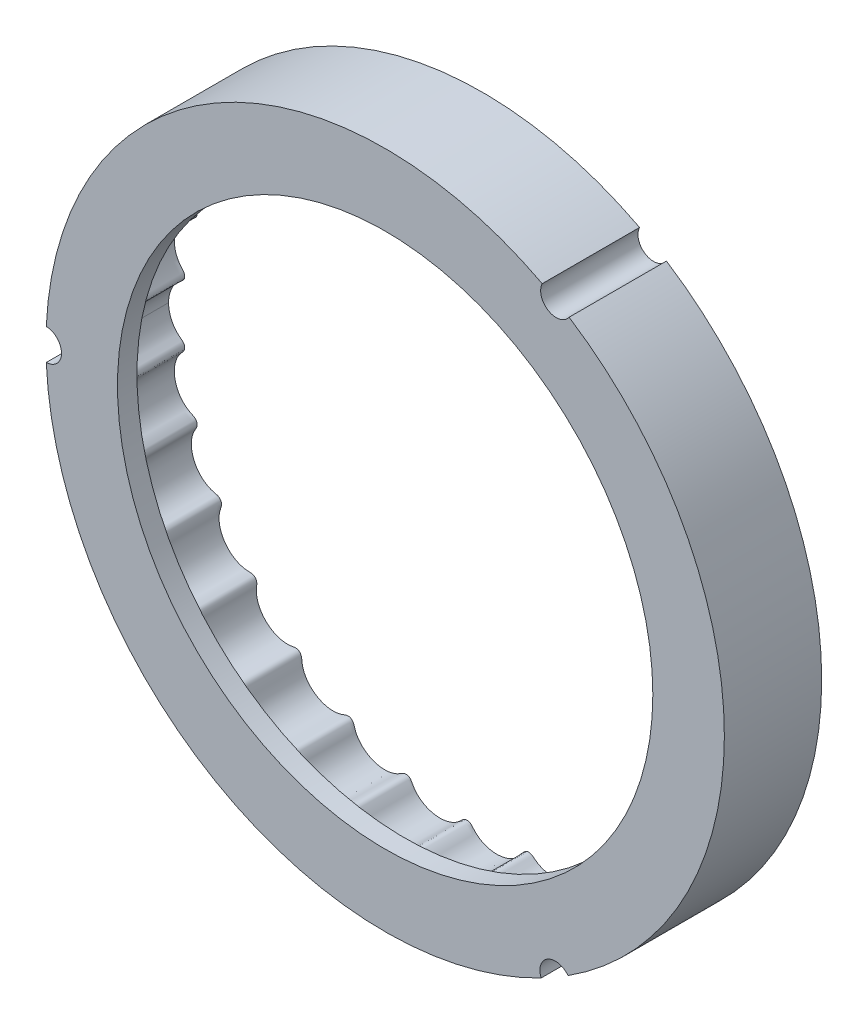
SolidWorks part; units mm, degrees
ref_plane "Plan de face" through (0, 0, 0) normal (0, 0, 1) x (1, 0, 0)
ref_plane "Plan de dessus" through (0, 0, 0) normal (0, 1, 0) x (1, 0, 0)
ref_plane "Plan de droite" through (0, 0, 0) normal (1, 0, 0) x (0, 0, -1)
sketch "Esquisse1" plane through (0, 0, 0) normal (0, 0, 1) x (1, 0, 0)
  line L0 (-1000, 0) -> (49000, 0) construction
  circle A1 centre (0, 0) radius 34.85
  spline S0 degree 4 poles (30.9263, 8.5917) (30.9244, 8.4726) (30.9128, 8.294) (30.8795, 8.0576) (30.8075, 7.7682) (30.7313, 7.5422) (30.6363, 7.3233) (30.5223, 7.1138) (30.4005, 6.9287) (30.2778, 6.7655) (30.1754, 6.608) (30.1146, 6.4469) (30.0971, 6.2542) (30.1421, 6.0755) (30.2337, 5.9301) (30.3636, 5.8076) (30.4814, 5.7308) (30.5967, 5.6632) (30.7272, 5.5824) (30.8546, 5.4968) (31.0375, 5.3568) (31.2617, 5.1464) (31.5493, 4.8022) (31.8437, 4.2901) (32.0606, 3.6436) (32.1377, 2.876) (32.0537, 2.1997) (31.8673, 1.6401) (31.6545, 1.2467) (31.4775, 0.9968) (31.3101, 0.8048) (31.1655, 0.661) (31.0397, 0.5491) (30.944, 0.4561) (30.882, 0.3799) (30.8461, 0.3281) (30.8149, 0.2732) (30.7893, 0.2154) (30.772, 0.1642) (30.7612, 0.1176) (30.7537, 0.0676) (30.7495, 0.0174) (30.7494, -0.0196) (30.7554, -0.0873) (30.767, -0.1466) (30.7842, -0.2016) (30.8067, -0.2559) (30.8409, -0.3211) (30.8874, -0.3891) (30.9471, -0.4581) (31.0185, -0.528) (31.0876, -0.5916) (31.174, -0.6713) (31.275, -0.7696) (31.4187, -0.925) (31.5905, -1.1493) (31.7652, -1.4406) (31.9227, -1.8045) (32.035, -2.1949) (32.0985, -2.6058) (32.1109, -3.0185) (32.074, -3.4266) (31.9897, -3.8245) (31.8596, -4.2068) (31.6858, -4.5663) (31.471, -4.8977) (31.2491, -5.1584) (31.0376, -5.3559) (30.847, -5.5028) (30.6865, -5.6097) (30.5113, -5.713) (30.3279, -5.8265) (30.1731, -5.9986) (30.0932, -6.2291) (30.1102, -6.46) (30.2005, -6.6565) (30.3192, -6.8188) (30.4296, -6.9724) (30.5569, -7.1717) (30.687, -7.4243) (30.8105, -7.7521) (30.9023, -8.158) (30.9393, -8.591) (30.9154, -9.0432) (30.8331, -9.4792) (30.6986, -9.8922) (30.5175, -10.2769) (30.2954, -10.6287) (30.0366, -10.942) (29.747, -11.2129) (29.4704, -11.4101) (29.2233, -11.5472) (29.008, -11.6414) (28.8315, -11.7068) (28.6421, -11.7692) (28.45, -11.8631) (28.2883, -12.027) (28.2103, -12.2249) (28.2035, -12.4054) (28.2368, -12.5701) (28.2938, -12.7158) (28.368, -12.8732) (28.4417, -13.0514) (28.5193, -13.2794) (28.5859, -13.5612) (28.6259, -13.9014) (28.6202, -14.2968) (28.5642, -14.6927) (28.4589, -15.0831) (28.3079, -15.4581) (28.1138, -15.8126) (27.8795, -16.1417) (27.6077, -16.4405) (27.3049, -16.7011) (26.9756, -16.9193) (26.6681, -17.0697) (26.3953, -17.1663) (26.1618, -17.2248) (25.972, -17.2589) (25.7701, -17.2839) (25.5569, -17.3186) (25.349, -17.4213) (25.1897, -17.6061) (25.1202, -17.827) (25.1307, -18.0426) (25.1768, -18.2381) (25.2169, -18.423) (25.254, -18.6564) (25.2723, -18.9399) (25.2546, -19.2896) (25.1768, -19.6983) (25.0382, -20.11) (24.8361, -20.5151) (24.5838, -20.8868) (24.2876, -21.2199) (23.9535, -21.5097) (23.5874, -21.7517) (23.2101, -21.9337) (22.8739, -22.0436) (22.5914, -22.1021) (22.3252, -22.1336) (22.1016, -22.1407) (21.8785, -22.1275) (21.6437, -22.1096) (21.4389, -22.1288) (21.235, -22.2214) (21.0721, -22.3967) (20.993, -22.6129) (20.9856, -22.8294) (20.9927, -23.0328) (20.9891, -23.2256) (20.9691, -23.4656) (20.9175, -23.7504) (20.8184, -24.0782) (20.6555, -24.4384) (20.4463, -24.779) (20.1313, -25.174) (19.6816, -25.5833) (19.1591, -25.8987) (18.5904, -26.1016) (18.1017, -26.1879) (17.7596, -26.203) (17.4709, -26.1826) (17.2335, -26.1428) (17.0458, -26.0984) (16.8505, -26.0411) (16.6399, -25.9918) (16.4106, -26.0101) (16.1979, -26.12) (16.0541, -26.2917) (15.9812, -26.4843) (15.9468, -26.6722) (15.9136, -26.8477) (15.8717, -27.0214) (15.8184, -27.1921) (15.7382, -27.4006) (15.5637, -27.7585) (15.2945, -28.1386) (14.9171, -28.5115) (14.4633, -28.8259) (14.0673, -29.0303) (13.6447, -29.1826) (13.2023, -29.278) (12.7692, -29.3104) (12.354, -29.2847) (12.0109, -29.2154) (11.7407, -29.1278) (11.5237, -29.0341) (11.3545, -28.9495) (11.1772, -28.8554) (10.9723, -28.7881) (10.7409, -28.7959) (10.5202, -28.8997) (10.3654, -29.0728) (10.2765, -29.2698) (10.2021, -29.4592) (10.1221, -29.6346) (10.0078, -29.8465) (9.8467, -30.087) (9.625, -30.3479) (9.2571, -30.6809) (8.748, -31.0055) (8.1785, -31.2248) (7.5795, -31.329) (7.0742, -31.3356) (6.6768, -31.2918) (6.2924, -31.1996) (5.9727, -31.0767) (5.7161, -30.9427) (5.5144, -30.8112) (5.3599, -30.6957) (5.2035, -30.5655) (5.0269, -30.4397) (4.8069, -30.3718) (4.5688, -30.3956) (4.3717, -30.5019) (4.2324, -30.653) (4.1276, -30.8125) (4.0272, -30.9603) (3.9195, -31.1029) (3.8025, -31.238) (3.6457, -31.3971) (3.3428, -31.6554) (2.8502, -31.9535) (2.2369, -32.1596) (1.5733, -32.2322) (1.0155, -32.1965) (0.5716, -32.1077) (0.1613, -31.9647) (-0.2092, -31.7754) (-0.4962, -31.5747) (-0.7089, -31.3863) (-0.8705, -31.2138) (-0.9919, -31.0688) (-1.1186, -30.9128) (-1.2838, -30.7736) (-1.5018, -30.6954) (-1.7453, -30.7105) (-1.9528, -30.8138) (-2.1099, -30.9617) (-2.2535, -31.1059) (-2.3968, -31.2349) (-2.5863, -31.3834) (-2.8299, -31.5395) (-3.1373, -31.6901) (-3.5116, -31.8163) (-3.9031, -31.8956) (-4.3058, -31.9269) (-4.7094, -31.9102) (-5.1084, -31.8461) (-5.4973, -31.7354) (-5.8703, -31.5791) (-6.2174, -31.3804) (-6.5332, -31.1424) (-6.7773, -30.902) (-6.9589, -30.6765) (-7.0914, -30.4753) (-7.1869, -30.3078) (-7.2659, -30.1527) (-7.3469, -30.0188) (-7.4577, -29.8924) (-7.6055, -29.7886) (-7.8103, -29.7311) (-8.0386, -29.7607) (-8.2296, -29.8563) (-8.3948, -29.9679) (-8.5547, -30.0672) (-8.7612, -30.1794) (-9.0211, -30.2905) (-9.3464, -30.3878) (-9.7381, -30.4504) (-10.1442, -30.4625) (-10.5582, -30.4222) (-10.9731, -30.3294) (-11.3818, -30.1823) (-11.7767, -29.98) (-12.1486, -29.7215) (-12.4679, -29.4266) (-12.7322, -29.1051) (-12.9152, -28.8064) (-13.0349, -28.5486) (-13.1142, -28.3258) (-13.1678, -28.1444) (-13.224, -27.9513) (-13.3256, -27.7603) (-13.4992, -27.6071) (-13.731, -27.5313) (-13.9616, -27.5503) (-14.1632, -27.6266) (-14.3522, -27.7017) (-14.535, -27.7628) (-14.7681, -27.8232) (-15.0538, -27.869) (-15.3957, -27.8843) (-15.7892, -27.8507) (-16.2785, -27.7463) (-16.7528, -27.5609) (-17.1946, -27.3015) (-17.5907, -26.9743) (-17.8764, -26.672) (-18.1159, -26.3439) (-18.3067, -25.9962) (-18.4295, -25.6796) (-18.5013, -25.4063) (-18.5394, -25.1743) (-18.559, -24.9871) (-18.5718, -24.7882) (-18.6117, -24.5785) (-18.7262, -24.3789) (-18.8959, -24.2506) (-19.068, -24.1957) (-19.2358, -24.1842) (-19.3915, -24.2014) (-19.5625, -24.2339) (-19.7534, -24.2613) (-19.9935, -24.2801) (-20.283, -24.2751) (-20.6226, -24.2297) (-21.0043, -24.1264) (-21.3741, -23.9741) (-21.7265, -23.7753) (-22.0523, -23.536) (-22.3477, -23.2602) (-22.6084, -22.9516) (-22.8306, -22.6144) (-23.008, -22.2566) (-23.138, -21.8836) (-23.2077, -21.5484) (-23.2339, -21.2603) (-23.2329, -21.0195) (-23.2189, -20.8273) (-23.1931, -20.6255) (-23.1714, -20.4109) (-23.2147, -20.1833) (-23.35, -19.9802) (-23.5441, -19.854) (-23.755, -19.8069) (-23.956, -19.8018) (-24.145, -19.7948) (-24.3804, -19.7731) (-24.6597, -19.7208) (-25.1025, -19.5837) (-25.5719, -19.3339) (-26.0033, -18.993) (-26.3759, -18.5716) (-26.6251, -18.2022) (-26.8231, -17.8067) (-26.9668, -17.3922) (-27.0498, -16.9817) (-27.0732, -16.6288) (-27.06, -16.3406) (-27.0307, -16.1192) (-26.9958, -15.9439) (-26.9493, -15.7714) (-26.894, -15.6014) (-26.8318, -15.421) (-26.7962, -15.2188) (-26.8307, -14.9976) (-26.9558, -14.7937) (-27.1431, -14.6595) (-27.3504, -14.5957) (-27.5492, -14.5518) (-27.7351, -14.5006) (-27.9627, -14.422) (-28.2261, -14.3016) (-28.5192, -14.1246) (-28.8279, -13.8775) (-29.1063, -13.5905) (-29.4109, -13.1873) (-29.6486, -12.7398) (-29.8135, -12.2607) (-29.9002, -11.7631) (-29.9203, -11.3641) (-29.8906, -10.9701) (-29.8207, -10.6349) (-29.7296, -10.3602) (-29.6324, -10.14) (-29.543, -9.9692) (-29.4389, -9.7943) (-29.3367, -9.6039) (-29.2926, -9.3762) (-29.3434, -9.1376) (-29.4773, -8.9486) (-29.655, -8.8263) (-29.838, -8.7434) (-30.0085, -8.6617) (-30.2156, -8.5478) (-30.4507, -8.3882) (-30.716, -8.1598) (-30.9909, -7.8477) (-31.231, -7.4857) (-31.427, -7.0776) (-31.5659, -6.6505) (-31.6473, -6.2122) (-31.6713, -5.7706) (-31.638, -5.3329) (-31.5503, -4.9233) (-31.4308, -4.5902) (-31.3037, -4.3313) (-31.1883, -4.14) (-31.0862, -3.9932) (-30.9747, -3.8536) (-30.8564, -3.7197) (-30.7286, -3.5777) (-30.6197, -3.4032) (-30.57, -3.1848) (-30.6111, -2.949) (-30.7353, -2.7553) (-30.9027, -2.6179) (-31.0677, -2.4988) (-31.2178, -2.3777) (-31.395, -2.2147) (-31.5882, -1.9992) (-31.757, -1.7611) (-31.8999, -1.5043) (-32.0017, -1.2787) (-32.0729, -1.0898) (-32.1322, -0.8972) (-32.1797, -0.7008) (-32.2109, -0.5276) (-32.2302, -0.3771) (-32.2413, -0.2512) (-32.2473, -0.1576) (-32.2503, -0.0299) (-32.2502, 0.0388) (-32.2466, 0.1794) (-32.2393, 0.2769) (-32.2254, 0.4211) (-32.2015, 0.5861) (-32.1629, 0.7796) (-32.104, 0.996) (-32.0305, 1.2085) (-31.9423, 1.415) (-31.8234, 1.6465) (-31.6896, 1.8577) (-31.544, 2.0481) (-31.3892, 2.217) (-31.2566, 2.3437) (-31.1158, 2.461) (-30.9692, 2.571) (-30.8116, 2.6874) (-30.6684, 2.8431) (-30.5791, 3.0569) (-30.5824, 3.2743) (-30.648, 3.4491) (-30.7462, 3.5961) (-30.8554, 3.7195) (-30.9782, 3.8564) (-31.1043, 4.0167) (-31.2467, 4.228) (-31.3916, 4.4977) (-31.5524, 4.9075) (-31.6691, 5.4709) (-31.6776, 6.1306) (-31.5281, 6.8579) (-31.2314, 7.526) (-30.8027, 8.104) (-30.3929, 8.4476) (-30.0923, 8.62) (-29.937, 8.6951) knots 0 0 0 0 0 0.003562 0.005342 0.007123 0.008904 0.010685 0.012466 0.014247 0.015519 0.016792 0.018065 0.019337 0.021229 0.022175 0.02312 0.024649 0.025414 0.026178 0.027707 0.029236 0.032293 0.035351 0.04107 0.046788 0.052507 0.058226 0.06127 0.064314 0.065836 0.067358 0.06888 0.070402 0.070873 0.071343 0.071813 0.072284 0.072754 0.073224 0.073459 0.073695 0.074165 0.074604 0.075042 0.075481 0.07592 0.076358 0.076797 0.077674 0.078377 0.079079 0.079782 0.080484 0.081889 0.083294 0.086104 0.088914 0.092014 0.095114 0.098215 0.101315 0.104325 0.107336 0.110347 0.113357 0.116235 0.119112 0.12055 0.121989 0.123428 0.124866 0.12664 0.128414 0.130187 0.13196 0.133373 0.134786 0.1362 0.137613 0.140439 0.143265 0.146639 0.150014 0.153388 0.156763 0.159865 0.162966 0.166068 0.169169 0.171979 0.174789 0.176194 0.177599 0.179004 0.180409 0.182167 0.183924 0.185706 0.186596 0.187487 0.188927 0.190366 0.191805 0.193245 0.196124 0.199002 0.202017 0.205033 0.208048 0.211063 0.214074 0.217086 0.220098 0.22311 0.225987 0.228865 0.230303 0.231742 0.233181 0.234619 0.236396 0.238172 0.239944 0.241716 0.243129 0.244541 0.245954 0.247367 0.250192 0.253017 0.256391 0.259764 0.263137 0.266511 0.269782 0.273052 0.276323 0.279594 0.282264 0.283598 0.284933 0.287603 0.288938 0.290273 0.291978 0.293684 0.295463 0.297243 0.298682 0.300121 0.30156 0.302999 0.305877 0.308756 0.311769 0.314783 0.317797 0.323824 0.32985 0.332862 0.33574 0.338618 0.340058 0.341497 0.342936 0.344375 0.346152 0.34793 0.349637 0.351344 0.352679 0.354014 0.355349 0.356684 0.358019 0.359354 0.362024 0.368567 0.371839 0.375111 0.378483 0.381856 0.385228 0.388601 0.391426 0.39425 0.395663 0.397075 0.398488 0.3999 0.401672 0.403443 0.40522 0.406997 0.408436 0.409875 0.411314 0.412753 0.415631 0.418509 0.421521 0.427546 0.433573 0.436587 0.439601 0.442616 0.445494 0.448372 0.449812 0.451251 0.45269 0.454129 0.455909 0.457689 0.459394 0.461099 0.462434 0.463768 0.465103 0.466438 0.467773 0.469108 0.471777 0.478318 0.484859 0.488232 0.491606 0.49498 0.498354 0.501179 0.504005 0.505418 0.50683 0.508243 0.509656 0.511429 0.513201 0.514977 0.516752 0.518191 0.519629 0.521068 0.522507 0.525384 0.528261 0.531273 0.534284 0.537295 0.540307 0.543322 0.546338 0.549353 0.552369 0.555248 0.558127 0.559566 0.561006 0.562445 0.563885 0.564776 0.565667 0.567449 0.569206 0.570963 0.572368 0.573772 0.575177 0.576582 0.579392 0.582202 0.585303 0.588404 0.591505 0.594606 0.597981 0.601356 0.604731 0.608106 0.610932 0.613759 0.615172 0.616585 0.617999 0.619412 0.621185 0.622958 0.624731 0.626505 0.627943 0.629382 0.63082 0.632259 0.635136 0.638013 0.641024 0.644034 0.650055 0.653155 0.656256 0.659357 0.662457 0.665267 0.668077 0.669482 0.670887 0.672292 0.673697 0.675453 0.677208 0.678992 0.679883 0.680775 0.682214 0.683654 0.685093 0.686533 0.689412 0.69229 0.695306 0.698322 0.701338 0.704354 0.707365 0.710376 0.713387 0.716398 0.719275 0.722153 0.723591 0.72503 0.726469 0.727907 0.729682 0.731457 0.73323 0.735002 0.736415 0.737828 0.739241 0.740654 0.74348 0.746306 0.753054 0.756428 0.759802 0.763072 0.766342 0.769612 0.772882 0.775551 0.776886 0.778221 0.779556 0.780891 0.782226 0.78356 0.785264 0.786968 0.788749 0.790529 0.791969 0.793408 0.794847 0.796287 0.799165 0.802044 0.805058 0.808073 0.811088 0.817114 0.820127 0.823139 0.826151 0.829028 0.831906 0.833345 0.834784 0.836223 0.837661 0.839438 0.841215 0.842986 0.844758 0.846171 0.847583 0.848996 0.850409 0.853234 0.856059 0.859432 0.862805 0.866178 0.86955 0.872822 0.876093 0.879364 0.882635 0.885305 0.88664 0.887975 0.88931 0.890645 0.89198 0.893315 0.895021 0.896727 0.898506 0.900284 0.901724 0.903163 0.904602 0.906041 0.908919 0.911797 0.913304 0.91481 0.916317 0.917824 0.91933 0.920837 0.92159 0.922344 0.923097 0.92385 0.924689 0.925528 0.926367 0.927206 0.928883 0.930561 0.932238 0.933916 0.935594 0.937271 0.94001 0.941379 0.942748 0.944117 0.945486 0.946856 0.948225 0.949976 0.951727 0.9536 0.954537 0.955474 0.956996 0.958518 0.96004 0.961563 0.964607 0.967651 0.973159 0.978666 0.984174 0.989682 0.994841 1 1 1 1 1 construction
  spline S1 degree 4 poles (30.75, 0) (30.75, -0.0125) (30.751, -0.0374) (30.7554, -0.0873) (30.767, -0.1466) (30.7842, -0.2016) (30.8067, -0.2559) (30.8409, -0.3211) (30.8874, -0.3891) (30.9471, -0.4581) (31.0185, -0.528) (31.0876, -0.5916) (31.174, -0.6713) (31.275, -0.7696) (31.4187, -0.925) (31.5905, -1.1493) (31.7652, -1.4406) (31.9227, -1.8045) (32.035, -2.1949) (32.0985, -2.6058) (32.1109, -3.0185) (32.074, -3.4266) (31.9897, -3.8245) (31.8596, -4.2068) (31.6858, -4.5663) (31.471, -4.8977) (31.2491, -5.1584) (31.0376, -5.3559) (30.847, -5.5028) (30.6865, -5.6097) (30.5113, -5.713) (30.3279, -5.8265) (30.1731, -5.9986) (30.0932, -6.2291) (30.1102, -6.46) (30.2005, -6.6565) (30.3192, -6.8188) (30.4296, -6.9724) (30.5569, -7.1717) (30.687, -7.4243) (30.8105, -7.7521) (30.9023, -8.158) (30.9393, -8.591) (30.9154, -9.0432) (30.8331, -9.4792) (30.6986, -9.8922) (30.5175, -10.2769) (30.2954, -10.6287) (30.0366, -10.942) (29.747, -11.2129) (29.4704, -11.4101) (29.2233, -11.5472) (29.008, -11.6414) (28.8315, -11.7068) (28.6421, -11.7692) (28.45, -11.8631) (28.2883, -12.027) (28.2103, -12.2249) (28.2035, -12.4054) (28.2368, -12.5701) (28.2938, -12.7158) (28.368, -12.8732) (28.4417, -13.0514) (28.5193, -13.2794) (28.5859, -13.5612) (28.6259, -13.9014) (28.6202, -14.2968) (28.5642, -14.6927) (28.4589, -15.0831) (28.3079, -15.4581) (28.1138, -15.8126) (27.8795, -16.1417) (27.6077, -16.4405) (27.3049, -16.7011) (26.9756, -16.9193) (26.6681, -17.0697) (26.3953, -17.1663) (26.1618, -17.2248) (25.972, -17.2589) (25.7701, -17.2839) (25.5569, -17.3186) (25.349, -17.4213) (25.1897, -17.6061) (25.1202, -17.827) (25.1307, -18.0426) (25.1768, -18.2381) (25.2169, -18.423) (25.254, -18.6564) (25.2723, -18.9399) (25.2546, -19.2896) (25.1768, -19.6983) (25.0382, -20.11) (24.8361, -20.5151) (24.5838, -20.8868) (24.2876, -21.2199) (23.9535, -21.5097) (23.5874, -21.7517) (23.2101, -21.9337) (22.8739, -22.0436) (22.5914, -22.1021) (22.3252, -22.1336) (22.1016, -22.1407) (21.8785, -22.1275) (21.6437, -22.1096) (21.4389, -22.1288) (21.235, -22.2214) (21.0721, -22.3967) (20.993, -22.6129) (20.9856, -22.8294) (20.9927, -23.0328) (20.9891, -23.2256) (20.9691, -23.4656) (20.9175, -23.7504) (20.8184, -24.0782) (20.6555, -24.4384) (20.4463, -24.779) (20.1313, -25.174) (19.6816, -25.5833) (19.1591, -25.8987) (18.5904, -26.1016) (18.1017, -26.1879) (17.7596, -26.203) (17.4709, -26.1826) (17.2335, -26.1428) (17.0458, -26.0984) (16.8505, -26.0411) (16.6399, -25.9918) (16.4106, -26.0101) (16.1979, -26.12) (16.0541, -26.2917) (15.9812, -26.4843) (15.9468, -26.6722) (15.9136, -26.8477) (15.8717, -27.0214) (15.8184, -27.1921) (15.7382, -27.4006) (15.5637, -27.7585) (15.2945, -28.1386) (14.9171, -28.5115) (14.4633, -28.8259) (14.0673, -29.0303) (13.6447, -29.1826) (13.2023, -29.278) (12.7692, -29.3104) (12.354, -29.2847) (12.0109, -29.2154) (11.7407, -29.1278) (11.5237, -29.0341) (11.3545, -28.9495) (11.1772, -28.8554) (10.9723, -28.7881) (10.7409, -28.7959) (10.5202, -28.8997) (10.3654, -29.0728) (10.2765, -29.2698) (10.2021, -29.4592) (10.1221, -29.6346) (10.0078, -29.8465) (9.8467, -30.087) (9.625, -30.3479) (9.2571, -30.6809) (8.748, -31.0055) (8.1785, -31.2248) (7.5795, -31.329) (7.0742, -31.3356) (6.6768, -31.2918) (6.2924, -31.1996) (5.9727, -31.0767) (5.7161, -30.9427) (5.5144, -30.8112) (5.3599, -30.6957) (5.2035, -30.5655) (5.0269, -30.4397) (4.8069, -30.3718) (4.5688, -30.3956) (4.3717, -30.5019) (4.2324, -30.653) (4.1276, -30.8125) (4.0272, -30.9603) (3.9195, -31.1029) (3.8025, -31.238) (3.6457, -31.3971) (3.3428, -31.6554) (2.8502, -31.9535) (2.2369, -32.1596) (1.5733, -32.2322) (1.0155, -32.1965) (0.5716, -32.1077) (0.1613, -31.9647) (-0.2092, -31.7754) (-0.4962, -31.5747) (-0.7089, -31.3863) (-0.8705, -31.2138) (-0.9919, -31.0688) (-1.1186, -30.9128) (-1.2838, -30.7736) (-1.5018, -30.6954) (-1.7453, -30.7105) (-1.9528, -30.8138) (-2.1099, -30.9617) (-2.2535, -31.1059) (-2.3968, -31.2349) (-2.5863, -31.3834) (-2.8299, -31.5395) (-3.1373, -31.6901) (-3.5116, -31.8163) (-3.9031, -31.8956) (-4.3058, -31.9269) (-4.7094, -31.9102) (-5.1084, -31.8461) (-5.4973, -31.7354) (-5.8703, -31.5791) (-6.2174, -31.3804) (-6.5332, -31.1424) (-6.7773, -30.902) (-6.9589, -30.6765) (-7.0914, -30.4753) (-7.1869, -30.3078) (-7.2659, -30.1527) (-7.3469, -30.0188) (-7.4577, -29.8924) (-7.6055, -29.7886) (-7.8103, -29.7311) (-8.0386, -29.7607) (-8.2296, -29.8563) (-8.3948, -29.9679) (-8.5547, -30.0672) (-8.7612, -30.1794) (-9.0211, -30.2905) (-9.3464, -30.3878) (-9.7381, -30.4504) (-10.1442, -30.4625) (-10.5582, -30.4222) (-10.9731, -30.3294) (-11.3818, -30.1823) (-11.7767, -29.98) (-12.1486, -29.7215) (-12.4679, -29.4266) (-12.7322, -29.1051) (-12.9152, -28.8064) (-13.0349, -28.5486) (-13.1142, -28.3258) (-13.1678, -28.1444) (-13.224, -27.9513) (-13.3256, -27.7603) (-13.4992, -27.6071) (-13.731, -27.5313) (-13.9616, -27.5503) (-14.1632, -27.6266) (-14.3522, -27.7017) (-14.535, -27.7628) (-14.7681, -27.8232) (-15.0538, -27.869) (-15.3957, -27.8843) (-15.7892, -27.8507) (-16.2785, -27.7463) (-16.7528, -27.5609) (-17.1946, -27.3015) (-17.5907, -26.9743) (-17.8764, -26.672) (-18.1159, -26.3439) (-18.3067, -25.9962) (-18.4295, -25.6796) (-18.5013, -25.4063) (-18.5394, -25.1743) (-18.559, -24.9871) (-18.5718, -24.7882) (-18.6117, -24.5785) (-18.7262, -24.3789) (-18.8959, -24.2506) (-19.068, -24.1957) (-19.2358, -24.1842) (-19.3915, -24.2014) (-19.5625, -24.2339) (-19.7534, -24.2613) (-19.9935, -24.2801) (-20.283, -24.2751) (-20.6226, -24.2297) (-21.0043, -24.1264) (-21.3741, -23.9741) (-21.7265, -23.7753) (-22.0523, -23.536) (-22.3477, -23.2602) (-22.6084, -22.9516) (-22.8306, -22.6144) (-23.008, -22.2566) (-23.138, -21.8836) (-23.2077, -21.5484) (-23.2339, -21.2603) (-23.2329, -21.0195) (-23.2189, -20.8273) (-23.1931, -20.6255) (-23.1714, -20.4109) (-23.2147, -20.1833) (-23.35, -19.9802) (-23.5441, -19.854) (-23.755, -19.8069) (-23.956, -19.8018) (-24.145, -19.7948) (-24.3804, -19.7731) (-24.6597, -19.7208) (-25.1025, -19.5837) (-25.5719, -19.3339) (-26.0033, -18.993) (-26.3759, -18.5716) (-26.6251, -18.2022) (-26.8231, -17.8067) (-26.9668, -17.3922) (-27.0498, -16.9817) (-27.0732, -16.6288) (-27.06, -16.3406) (-27.0307, -16.1192) (-26.9958, -15.9439) (-26.9493, -15.7714) (-26.894, -15.6014) (-26.8318, -15.421) (-26.7962, -15.2188) (-26.8307, -14.9976) (-26.9558, -14.7937) (-27.1431, -14.6595) (-27.3504, -14.5957) (-27.5492, -14.5518) (-27.7351, -14.5006) (-27.9627, -14.422) (-28.2261, -14.3016) (-28.5192, -14.1246) (-28.8279, -13.8775) (-29.1063, -13.5905) (-29.4109, -13.1873) (-29.6486, -12.7398) (-29.8135, -12.2607) (-29.9002, -11.7631) (-29.9203, -11.3641) (-29.8906, -10.9701) (-29.8207, -10.6349) (-29.7296, -10.3602) (-29.6324, -10.14) (-29.543, -9.9692) (-29.4389, -9.7943) (-29.3367, -9.6039) (-29.2926, -9.3762) (-29.3434, -9.1376) (-29.4773, -8.9486) (-29.655, -8.8263) (-29.838, -8.7434) (-30.0085, -8.6617) (-30.2156, -8.5478) (-30.4507, -8.3882) (-30.716, -8.1598) (-30.9909, -7.8477) (-31.231, -7.4857) (-31.427, -7.0776) (-31.5659, -6.6505) (-31.6473, -6.2122) (-31.6713, -5.7706) (-31.638, -5.3329) (-31.5503, -4.9233) (-31.4308, -4.5902) (-31.3037, -4.3313) (-31.1883, -4.14) (-31.0862, -3.9932) (-30.9747, -3.8536) (-30.8564, -3.7197) (-30.7286, -3.5777) (-30.6197, -3.4032) (-30.57, -3.1848) (-30.6111, -2.949) (-30.7353, -2.7553) (-30.9027, -2.6179) (-31.0677, -2.4988) (-31.2178, -2.3777) (-31.395, -2.2147) (-31.5882, -1.9992) (-31.757, -1.7611) (-31.8999, -1.5043) (-32.0017, -1.2787) (-32.0729, -1.0898) (-32.1322, -0.8972) (-32.1797, -0.7008) (-32.2109, -0.5276) (-32.2302, -0.3771) (-32.2413, -0.2512) (-32.2473, -0.1576) (-32.2495, -0.0645) (-32.25, -0.0214) (-32.25, 0) knots 0.074165 0.074165 0.074165 0.074165 0.074165 0.074604 0.075042 0.075481 0.07592 0.076358 0.076797 0.077674 0.078377 0.079079 0.079782 0.080484 0.081889 0.083294 0.086104 0.088914 0.092014 0.095114 0.098215 0.101315 0.104325 0.107336 0.110347 0.113357 0.116235 0.119112 0.12055 0.121989 0.123428 0.124866 0.12664 0.128414 0.130187 0.13196 0.133373 0.134786 0.1362 0.137613 0.140439 0.143265 0.146639 0.150014 0.153388 0.156763 0.159865 0.162966 0.166068 0.169169 0.171979 0.174789 0.176194 0.177599 0.179004 0.180409 0.182167 0.183924 0.185706 0.186596 0.187487 0.188927 0.190366 0.191805 0.193245 0.196124 0.199002 0.202017 0.205033 0.208048 0.211063 0.214074 0.217086 0.220098 0.22311 0.225987 0.228865 0.230303 0.231742 0.233181 0.234619 0.236396 0.238172 0.239944 0.241716 0.243129 0.244541 0.245954 0.247367 0.250192 0.253017 0.256391 0.259764 0.263137 0.266511 0.269782 0.273052 0.276323 0.279594 0.282264 0.283598 0.284933 0.287603 0.288938 0.290273 0.291978 0.293684 0.295463 0.297243 0.298682 0.300121 0.30156 0.302999 0.305877 0.308756 0.311769 0.314783 0.317797 0.323824 0.32985 0.332862 0.33574 0.338618 0.340058 0.341497 0.342936 0.344375 0.346152 0.34793 0.349637 0.351344 0.352679 0.354014 0.355349 0.356684 0.358019 0.359354 0.362024 0.368567 0.371839 0.375111 0.378483 0.381856 0.385228 0.388601 0.391426 0.39425 0.395663 0.397075 0.398488 0.3999 0.401672 0.403443 0.40522 0.406997 0.408436 0.409875 0.411314 0.412753 0.415631 0.418509 0.421521 0.427546 0.433573 0.436587 0.439601 0.442616 0.445494 0.448372 0.449812 0.451251 0.45269 0.454129 0.455909 0.457689 0.459394 0.461099 0.462434 0.463768 0.465103 0.466438 0.467773 0.469108 0.471777 0.478318 0.484859 0.488232 0.491606 0.49498 0.498354 0.501179 0.504005 0.505418 0.50683 0.508243 0.509656 0.511429 0.513201 0.514977 0.516752 0.518191 0.519629 0.521068 0.522507 0.525384 0.528261 0.531273 0.534284 0.537295 0.540307 0.543322 0.546338 0.549353 0.552369 0.555248 0.558127 0.559566 0.561006 0.562445 0.563885 0.564776 0.565667 0.567449 0.569206 0.570963 0.572368 0.573772 0.575177 0.576582 0.579392 0.582202 0.585303 0.588404 0.591505 0.594606 0.597981 0.601356 0.604731 0.608106 0.610932 0.613759 0.615172 0.616585 0.617999 0.619412 0.621185 0.622958 0.624731 0.626505 0.627943 0.629382 0.63082 0.632259 0.635136 0.638013 0.641024 0.644034 0.650055 0.653155 0.656256 0.659357 0.662457 0.665267 0.668077 0.669482 0.670887 0.672292 0.673697 0.675453 0.677208 0.678992 0.679883 0.680775 0.682214 0.683654 0.685093 0.686533 0.689412 0.69229 0.695306 0.698322 0.701338 0.704354 0.707365 0.710376 0.713387 0.716398 0.719275 0.722153 0.723591 0.72503 0.726469 0.727907 0.729682 0.731457 0.73323 0.735002 0.736415 0.737828 0.739241 0.740654 0.74348 0.746306 0.753054 0.756428 0.759802 0.763072 0.766342 0.769612 0.772882 0.775551 0.776886 0.778221 0.779556 0.780891 0.782226 0.78356 0.785264 0.786968 0.788749 0.790529 0.791969 0.793408 0.794847 0.796287 0.799165 0.802044 0.805058 0.808073 0.811088 0.817114 0.820127 0.823139 0.826151 0.829028 0.831906 0.833345 0.834784 0.836223 0.837661 0.839438 0.841215 0.842986 0.844758 0.846171 0.847583 0.848996 0.850409 0.853234 0.856059 0.859432 0.862805 0.866178 0.86955 0.872822 0.876093 0.879364 0.882635 0.885305 0.88664 0.887975 0.88931 0.890645 0.89198 0.893315 0.895021 0.896727 0.898506 0.900284 0.901724 0.903163 0.904602 0.906041 0.908919 0.911797 0.913304 0.91481 0.916317 0.917824 0.91933 0.920837 0.92159 0.922344 0.923097 0.92385 0.92385 0.92385 0.92385 0.92385
  spline S2 degree 4 poles (30.75, 0) (30.75, 0.0125) (30.751, 0.0374) (30.7554, 0.0873) (30.767, 0.1466) (30.7842, 0.2016) (30.8067, 0.2559) (30.8409, 0.3211) (30.8874, 0.3891) (30.9471, 0.4581) (31.0185, 0.528) (31.0876, 0.5916) (31.174, 0.6713) (31.275, 0.7696) (31.4187, 0.925) (31.5905, 1.1493) (31.7652, 1.4406) (31.9227, 1.8045) (32.035, 2.1949) (32.0985, 2.6058) (32.1109, 3.0185) (32.074, 3.4266) (31.9897, 3.8245) (31.8596, 4.2068) (31.6858, 4.5663) (31.471, 4.8977) (31.2491, 5.1584) (31.0376, 5.3559) (30.847, 5.5028) (30.6865, 5.6097) (30.5113, 5.713) (30.3279, 5.8265) (30.1731, 5.9986) (30.0932, 6.2291) (30.1102, 6.46) (30.2005, 6.6565) (30.3192, 6.8188) (30.4296, 6.9724) (30.5569, 7.1717) (30.687, 7.4243) (30.8105, 7.7521) (30.9023, 8.158) (30.9393, 8.591) (30.9154, 9.0432) (30.8331, 9.4792) (30.6986, 9.8922) (30.5175, 10.2769) (30.2954, 10.6287) (30.0366, 10.942) (29.747, 11.2129) (29.4704, 11.4101) (29.2233, 11.5472) (29.008, 11.6414) (28.8315, 11.7068) (28.6421, 11.7692) (28.45, 11.8631) (28.2883, 12.027) (28.2103, 12.2249) (28.2035, 12.4054) (28.2368, 12.5701) (28.2938, 12.7158) (28.368, 12.8732) (28.4417, 13.0514) (28.5193, 13.2794) (28.5859, 13.5612) (28.6259, 13.9014) (28.6202, 14.2968) (28.5642, 14.6927) (28.4589, 15.0831) (28.3079, 15.4581) (28.1138, 15.8126) (27.8795, 16.1417) (27.6077, 16.4405) (27.3049, 16.7011) (26.9756, 16.9193) (26.6681, 17.0697) (26.3953, 17.1663) (26.1618, 17.2248) (25.972, 17.2589) (25.7701, 17.2839) (25.5569, 17.3186) (25.349, 17.4213) (25.1897, 17.6061) (25.1202, 17.827) (25.1307, 18.0426) (25.1768, 18.2381) (25.2169, 18.423) (25.254, 18.6564) (25.2723, 18.9399) (25.2546, 19.2896) (25.1768, 19.6983) (25.0382, 20.11) (24.8361, 20.5151) (24.5838, 20.8868) (24.2876, 21.2199) (23.9535, 21.5097) (23.5874, 21.7517) (23.2101, 21.9337) (22.8739, 22.0436) (22.5914, 22.1021) (22.3252, 22.1336) (22.1016, 22.1407) (21.8785, 22.1275) (21.6437, 22.1096) (21.4389, 22.1288) (21.235, 22.2214) (21.0721, 22.3967) (20.993, 22.6129) (20.9856, 22.8294) (20.9927, 23.0328) (20.9891, 23.2256) (20.9691, 23.4656) (20.9175, 23.7504) (20.8184, 24.0782) (20.6555, 24.4384) (20.4463, 24.779) (20.1313, 25.174) (19.6816, 25.5833) (19.1591, 25.8987) (18.5904, 26.1016) (18.1017, 26.1879) (17.7596, 26.203) (17.4709, 26.1826) (17.2335, 26.1428) (17.0458, 26.0984) (16.8505, 26.0411) (16.6399, 25.9918) (16.4106, 26.0101) (16.1979, 26.12) (16.0541, 26.2917) (15.9812, 26.4843) (15.9468, 26.6722) (15.9136, 26.8477) (15.8717, 27.0214) (15.8184, 27.1921) (15.7382, 27.4006) (15.5637, 27.7585) (15.2945, 28.1386) (14.9171, 28.5115) (14.4633, 28.8259) (14.0673, 29.0303) (13.6447, 29.1826) (13.2023, 29.278) (12.7692, 29.3104) (12.354, 29.2847) (12.0109, 29.2154) (11.7407, 29.1278) (11.5237, 29.0341) (11.3545, 28.9495) (11.1772, 28.8554) (10.9723, 28.7881) (10.7409, 28.7959) (10.5202, 28.8997) (10.3654, 29.0728) (10.2765, 29.2698) (10.2021, 29.4592) (10.1221, 29.6346) (10.0078, 29.8465) (9.8467, 30.087) (9.625, 30.3479) (9.2571, 30.6809) (8.748, 31.0055) (8.1785, 31.2248) (7.5795, 31.329) (7.0742, 31.3356) (6.6768, 31.2918) (6.2924, 31.1996) (5.9727, 31.0767) (5.7161, 30.9427) (5.5144, 30.8112) (5.3599, 30.6957) (5.2035, 30.5655) (5.0269, 30.4397) (4.8069, 30.3718) (4.5688, 30.3956) (4.3717, 30.5019) (4.2324, 30.653) (4.1276, 30.8125) (4.0272, 30.9603) (3.9195, 31.1029) (3.8025, 31.238) (3.6457, 31.3971) (3.3428, 31.6554) (2.8502, 31.9535) (2.2369, 32.1596) (1.5733, 32.2322) (1.0155, 32.1965) (0.5716, 32.1077) (0.1613, 31.9647) (-0.2092, 31.7754) (-0.4962, 31.5747) (-0.7089, 31.3863) (-0.8705, 31.2138) (-0.9919, 31.0688) (-1.1186, 30.9128) (-1.2838, 30.7736) (-1.5018, 30.6954) (-1.7453, 30.7105) (-1.9528, 30.8138) (-2.1099, 30.9617) (-2.2535, 31.1059) (-2.3968, 31.2349) (-2.5863, 31.3834) (-2.8299, 31.5395) (-3.1373, 31.6901) (-3.5116, 31.8163) (-3.9031, 31.8956) (-4.3058, 31.9269) (-4.7094, 31.9102) (-5.1084, 31.8461) (-5.4973, 31.7354) (-5.8703, 31.5791) (-6.2174, 31.3804) (-6.5332, 31.1424) (-6.7773, 30.902) (-6.9589, 30.6765) (-7.0914, 30.4753) (-7.1869, 30.3078) (-7.2659, 30.1527) (-7.3469, 30.0188) (-7.4577, 29.8924) (-7.6055, 29.7886) (-7.8103, 29.7311) (-8.0386, 29.7607) (-8.2296, 29.8563) (-8.3948, 29.9679) (-8.5547, 30.0672) (-8.7612, 30.1794) (-9.0211, 30.2905) (-9.3464, 30.3878) (-9.7381, 30.4504) (-10.1442, 30.4625) (-10.5582, 30.4222) (-10.9731, 30.3294) (-11.3818, 30.1823) (-11.7767, 29.98) (-12.1486, 29.7215) (-12.4679, 29.4266) (-12.7322, 29.1051) (-12.9152, 28.8064) (-13.0349, 28.5486) (-13.1142, 28.3258) (-13.1678, 28.1444) (-13.224, 27.9513) (-13.3256, 27.7603) (-13.4992, 27.6071) (-13.731, 27.5313) (-13.9616, 27.5503) (-14.1632, 27.6266) (-14.3522, 27.7017) (-14.535, 27.7628) (-14.7681, 27.8232) (-15.0538, 27.869) (-15.3957, 27.8843) (-15.7892, 27.8507) (-16.2785, 27.7463) (-16.7528, 27.5609) (-17.1946, 27.3015) (-17.5907, 26.9743) (-17.8764, 26.672) (-18.1159, 26.3439) (-18.3067, 25.9962) (-18.4295, 25.6796) (-18.5013, 25.4063) (-18.5394, 25.1743) (-18.559, 24.9871) (-18.5718, 24.7882) (-18.6117, 24.5785) (-18.7262, 24.3789) (-18.8959, 24.2506) (-19.068, 24.1957) (-19.2358, 24.1842) (-19.3915, 24.2014) (-19.5625, 24.2339) (-19.7534, 24.2613) (-19.9935, 24.2801) (-20.283, 24.2751) (-20.6226, 24.2297) (-21.0043, 24.1264) (-21.3741, 23.9741) (-21.7265, 23.7753) (-22.0523, 23.536) (-22.3477, 23.2602) (-22.6084, 22.9516) (-22.8306, 22.6144) (-23.008, 22.2566) (-23.138, 21.8836) (-23.2077, 21.5484) (-23.2339, 21.2603) (-23.2329, 21.0195) (-23.2189, 20.8273) (-23.1931, 20.6255) (-23.1714, 20.4109) (-23.2147, 20.1833) (-23.35, 19.9802) (-23.5441, 19.854) (-23.755, 19.8069) (-23.956, 19.8018) (-24.145, 19.7948) (-24.3804, 19.7731) (-24.6597, 19.7208) (-25.1025, 19.5837) (-25.5719, 19.3339) (-26.0033, 18.993) (-26.3759, 18.5716) (-26.6251, 18.2022) (-26.8231, 17.8067) (-26.9668, 17.3922) (-27.0498, 16.9817) (-27.0732, 16.6288) (-27.06, 16.3406) (-27.0307, 16.1192) (-26.9958, 15.9439) (-26.9493, 15.7714) (-26.894, 15.6014) (-26.8318, 15.421) (-26.7962, 15.2188) (-26.8307, 14.9976) (-26.9558, 14.7937) (-27.1431, 14.6595) (-27.3504, 14.5957) (-27.5492, 14.5518) (-27.7351, 14.5006) (-27.9627, 14.422) (-28.2261, 14.3016) (-28.5192, 14.1246) (-28.8279, 13.8775) (-29.1063, 13.5905) (-29.4109, 13.1873) (-29.6486, 12.7398) (-29.8135, 12.2607) (-29.9002, 11.7631) (-29.9203, 11.3641) (-29.8906, 10.9701) (-29.8207, 10.6349) (-29.7296, 10.3602) (-29.6324, 10.14) (-29.543, 9.9692) (-29.4389, 9.7943) (-29.3367, 9.6039) (-29.2926, 9.3762) (-29.3434, 9.1376) (-29.4773, 8.9486) (-29.655, 8.8263) (-29.838, 8.7434) (-30.0085, 8.6617) (-30.2156, 8.5478) (-30.4507, 8.3882) (-30.716, 8.1598) (-30.9909, 7.8477) (-31.231, 7.4857) (-31.427, 7.0776) (-31.5659, 6.6505) (-31.6473, 6.2122) (-31.6713, 5.7706) (-31.638, 5.3329) (-31.5503, 4.9233) (-31.4308, 4.5902) (-31.3037, 4.3313) (-31.1883, 4.14) (-31.0862, 3.9932) (-30.9747, 3.8536) (-30.8564, 3.7197) (-30.7286, 3.5777) (-30.6197, 3.4032) (-30.57, 3.1848) (-30.6111, 2.949) (-30.7353, 2.7553) (-30.9027, 2.6179) (-31.0677, 2.4988) (-31.2178, 2.3777) (-31.395, 2.2147) (-31.5882, 1.9992) (-31.757, 1.7611) (-31.8999, 1.5043) (-32.0017, 1.2787) (-32.0729, 1.0898) (-32.1322, 0.8972) (-32.1797, 0.7008) (-32.2109, 0.5276) (-32.2302, 0.3771) (-32.2413, 0.2512) (-32.2473, 0.1576) (-32.2495, 0.0645) (-32.25, 0.0214) (-32.25, 0) knots 0.074165 0.074165 0.074165 0.074165 0.074165 0.074604 0.075042 0.075481 0.07592 0.076358 0.076797 0.077674 0.078377 0.079079 0.079782 0.080484 0.081889 0.083294 0.086104 0.088914 0.092014 0.095114 0.098215 0.101315 0.104325 0.107336 0.110347 0.113357 0.116235 0.119112 0.12055 0.121989 0.123428 0.124866 0.12664 0.128414 0.130187 0.13196 0.133373 0.134786 0.1362 0.137613 0.140439 0.143265 0.146639 0.150014 0.153388 0.156763 0.159865 0.162966 0.166068 0.169169 0.171979 0.174789 0.176194 0.177599 0.179004 0.180409 0.182167 0.183924 0.185706 0.186596 0.187487 0.188927 0.190366 0.191805 0.193245 0.196124 0.199002 0.202017 0.205033 0.208048 0.211063 0.214074 0.217086 0.220098 0.22311 0.225987 0.228865 0.230303 0.231742 0.233181 0.234619 0.236396 0.238172 0.239944 0.241716 0.243129 0.244541 0.245954 0.247367 0.250192 0.253017 0.256391 0.259764 0.263137 0.266511 0.269782 0.273052 0.276323 0.279594 0.282264 0.283598 0.284933 0.287603 0.288938 0.290273 0.291978 0.293684 0.295463 0.297243 0.298682 0.300121 0.30156 0.302999 0.305877 0.308756 0.311769 0.314783 0.317797 0.323824 0.32985 0.332862 0.33574 0.338618 0.340058 0.341497 0.342936 0.344375 0.346152 0.34793 0.349637 0.351344 0.352679 0.354014 0.355349 0.356684 0.358019 0.359354 0.362024 0.368567 0.371839 0.375111 0.378483 0.381856 0.385228 0.388601 0.391426 0.39425 0.395663 0.397075 0.398488 0.3999 0.401672 0.403443 0.40522 0.406997 0.408436 0.409875 0.411314 0.412753 0.415631 0.418509 0.421521 0.427546 0.433573 0.436587 0.439601 0.442616 0.445494 0.448372 0.449812 0.451251 0.45269 0.454129 0.455909 0.457689 0.459394 0.461099 0.462434 0.463768 0.465103 0.466438 0.467773 0.469108 0.471777 0.478318 0.484859 0.488232 0.491606 0.49498 0.498354 0.501179 0.504005 0.505418 0.50683 0.508243 0.509656 0.511429 0.513201 0.514977 0.516752 0.518191 0.519629 0.521068 0.522507 0.525384 0.528261 0.531273 0.534284 0.537295 0.540307 0.543322 0.546338 0.549353 0.552369 0.555248 0.558127 0.559566 0.561006 0.562445 0.563885 0.564776 0.565667 0.567449 0.569206 0.570963 0.572368 0.573772 0.575177 0.576582 0.579392 0.582202 0.585303 0.588404 0.591505 0.594606 0.597981 0.601356 0.604731 0.608106 0.610932 0.613759 0.615172 0.616585 0.617999 0.619412 0.621185 0.622958 0.624731 0.626505 0.627943 0.629382 0.63082 0.632259 0.635136 0.638013 0.641024 0.644034 0.650055 0.653155 0.656256 0.659357 0.662457 0.665267 0.668077 0.669482 0.670887 0.672292 0.673697 0.675453 0.677208 0.678992 0.679883 0.680775 0.682214 0.683654 0.685093 0.686533 0.689412 0.69229 0.695306 0.698322 0.701338 0.704354 0.707365 0.710376 0.713387 0.716398 0.719275 0.722153 0.723591 0.72503 0.726469 0.727907 0.729682 0.731457 0.73323 0.735002 0.736415 0.737828 0.739241 0.740654 0.74348 0.746306 0.753054 0.756428 0.759802 0.763072 0.766342 0.769612 0.772882 0.775551 0.776886 0.778221 0.779556 0.780891 0.782226 0.78356 0.785264 0.786968 0.788749 0.790529 0.791969 0.793408 0.794847 0.796287 0.799165 0.802044 0.805058 0.808073 0.811088 0.817114 0.820127 0.823139 0.826151 0.829028 0.831906 0.833345 0.834784 0.836223 0.837661 0.839438 0.841215 0.842986 0.844758 0.846171 0.847583 0.848996 0.850409 0.853234 0.856059 0.859432 0.862805 0.866178 0.86955 0.872822 0.876093 0.879364 0.882635 0.885305 0.88664 0.887975 0.88931 0.890645 0.89198 0.893315 0.895021 0.896727 0.898506 0.900284 0.901724 0.903163 0.904602 0.906041 0.908919 0.911797 0.913304 0.91481 0.916317 0.917824 0.91933 0.920837 0.92159 0.922344 0.923097 0.92385 0.92385 0.92385 0.92385 0.92385
  dimension "D1" = 69.7
extrude "Boss.-Extru.1" add sketch "Esquisse1" along normal blind 8
sketch "Esquisse3" plane through (0, 0, 8) normal (0, 0, 1) x (1, 0, 0)
  circle A0 centre (0, 0) radius 27.5
  circle A1 centre (0, 0) radius 34.85
  circle A2 centre (0, 0) radius 34.85 construction
  dimension "D1" = 55
extrude "Boss.-Extru.2" add sketch "Esquisse3" along normal blind 2
sketch "Esquisse4" plane through (0, 0, 10) normal (0, 0, 1) x (1, 0, 0)
  circle A0 centre (-34.85, 0) radius 1.6
  circle A1 centre (0, 0) radius 34.85 construction
  circle A10 centre (17.575, 30.181) radius 1.6
  circle A11 centre (17.5, -30.3109) radius 1.6
  point P11 (0.075, -0.0433)
  dimension "D1" = 3.2
  dimension "D2" = 3
extrude "Enlèv. mat.-Extru.2" cut sketch "Esquisse4" against normal through all
equation "\"R\" = 32'Radius of the rotor"
equation "\"E\"= 0.75'Eccentricity from input shaft to center of rotor"
equation "\"Rr\"= 0.5'Roller radius"
equation "\"N\" = 32'Amount of rollers"
